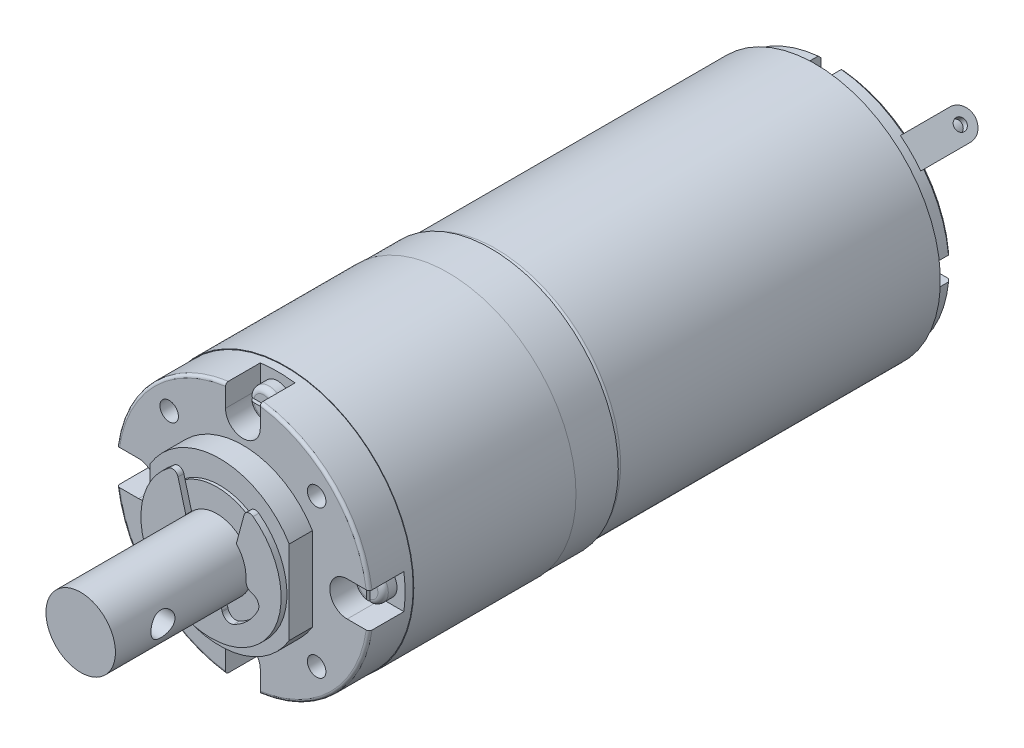
SolidWorks part; units mm, degrees
ref_plane "Front Plane" through (0, 0, 0) normal (0, 0, 1) x (1, 0, 0)
ref_plane "Top Plane" through (0, 0, 0) normal (0, 1, 0) x (1, 0, 0)
ref_plane "Right Plane" through (0, 0, 0) normal (1, 0, 0) x (0, 0, -1)
sketch "Sketch1" plane through (0, 0, 0) normal (0, 0, 1) x (1, 0, 0)
  circle A0 centre (0, 0) radius 11
  dimension "D1" = 22
extrude "Boss-Extrude1" add sketch "Sketch1" along normal mid plane 50.9
ref_plane "Plane1" through (0, 0, 4.05) normal (0, 0, -1) x (-1, 0, 0)
sketch "Sketch2" plane through (0, 0, 4.05) normal (0, 0, -1) x (-1, 0, 0)
  circle A0 centre (0, 0) radius 10.8
  circle A1 centre (0, 0) radius 11
  dimension "D1" = 22
  dimension "D2" = 21.6
extrude "Cut-Extrude1" cut sketch "Sketch2" along normal through all
ref_axis "Axis2" through (0, 0, -32.7585) along (0, 0, 1)
sketch "Sketch3" plane through (0, 0, 0) normal (1, 0, 0) x (0, 0, -1)
  line L0 (-4.05, 10.4) -> (-4.05, 10.3)
  line L1 (-3.55, 10.8) -> (-4.05, 10.8)
  line L2 (-4.05, -10.8) -> (-4.05, 10.8) construction
  line L3 (-4.05, 10.3) -> (-3.55, 10.3) construction
  line L4 (-3.55, 10.3) -> (-3.55, 10.8) construction
  line L5 (-3.55, 10.8) -> (-3.65, 10.8)
  line L6 (-4.05, -11) -> (-4.05, 11) construction
  line L7 (-4.05, 10.8) -> (-4.05, 10.3)
  arc A0 (-4.05, 10.4) -> (-3.65, 10.8) centre (-3.65, 10.4) cw
  dimension "D3" = 0.4
  dimension "D1" = 10.3
  dimension "D2" = 0.5
sketch "Sketch5" plane through (0, 0, 25.45) normal (0, 0, 1) x (1, 0, 0)
  line L0 (-1.5, 9) -> (-1.5, 10.8972)
  line L1 (1.5, 9) -> (1.5, 10.8972)
  line L2 (9, 1.5) -> (10.8972, 1.5)
  line L3 (9, -1.5) -> (10.8972, -1.5)
  line L4 (1.5, -9) -> (1.5, -10.8972)
  line L5 (-1.5, -9) -> (-1.5, -10.8972)
  line L6 (-9, -1.5) -> (-10.8972, -1.5)
  line L7 (-9, 1.5) -> (-10.8972, 1.5)
  circle A0 centre (0, 0) radius 9 construction
  arc A2 (-1.5, 9) -> (1.5, 9) centre (0, 9) ccw
  arc A3 (1.5, 10.8972) -> (-1.5, 10.8972) centre (0, 0) ccw
  arc A4 (9, 1.5) -> (9, -1.5) centre (9, 0) ccw
  arc A5 (10.8972, -1.5) -> (10.8972, 1.5) centre (0, 0) ccw
  arc A6 (1.5, -9) -> (-1.5, -9) centre (0, -9) ccw
  arc A7 (-1.5, -10.8972) -> (1.5, -10.8972) centre (0, 0) ccw
  arc A8 (-9, -1.5) -> (-9, 1.5) centre (-9, 0) ccw
  arc A9 (-10.8972, 1.5) -> (-10.8972, -1.5) centre (0, 0) ccw
  circle A10 centre (-6.364, 6.364) radius 0.8
  circle A11 centre (6.364, 6.364) radius 0.8
  circle A12 centre (6.364, -6.364) radius 0.8
  circle A13 centre (-6.364, -6.364) radius 0.8
  point P26 (0, 0)
  point P35 (0, 0)
  dimension "D1" = 18
  dimension "D2" = 1.5
  dimension "D3" = 11
  dimension "D6" = 1.6
  dimension "D5" = 45
  dimension "D4" = 4
  dimension "D7" = 4
extrude "Cut-Extrude2" cut sketch "Sketch5" against normal blind 3
revolve "Cut-Revolve3" cut sketch "Sketch3" angle 360 about axis through (0, 0, -32.7585) along (0, 0, 1)
sketch "Sketch6" plane through (0, 0, 25.45) normal (0, 0, 1) x (1, 0, 0)
  line L0 (-6, -3.6056) -> (-6, 3.6056)
  line L1 (6, -3.6056) -> (6, 3.6056)
  arc A0 (-6, -3.6056) -> (6, -3.6056) centre (0, 0) ccw
  arc A1 (6, 3.6056) -> (-6, 3.6056) centre (0, 0) ccw
  point P6 (-6, 0)
  point P9 (6, 0)
  dimension "D1" = 14
  dimension "D2" = 6
  dimension "D3" = 6
extrude "Boss-Extrude2" add sketch "Sketch6" along normal blind 2
sketch "Sketch7" plane through (0, 0, 27.45) normal (0, 0, 1) x (1, 0, 0)
  circle A0 centre (0, 0) radius 3
  dimension "D1" = 6
extrude "Boss-Extrude3" add sketch "Sketch7" along normal blind 12
ref_plane "Plane3" through (0, 0, 22.45) normal (0, 0, 1) x (1, 0, 0)
ref_plane "Plane4" through (0, 9, 0) normal (0, 1, 0) x (1, 0, 0)
sketch "Sketch9" plane through (0, 9, 0) normal (0, 1, 0) x (1, 0, 0)
  line L0 (0, -22.45) -> (0, -23.65)
  line L1 (-15.9774, -22.45) -> (15.9774, -22.45) construction
  line L2 (0, 32.7585) -> (0, -39.3925) construction
  line L3 (0, -23.65) -> (0.85, -23.65)
  line L4 (1.3, -23.2) -> (1.3, -22.45)
  line L5 (1.3, -22.45) -> (0, -22.45)
  arc A0 (1.3, -23.2) -> (0.85, -23.65) centre (0.85, -23.2) cw
  dimension "D1" = 0.45
  dimension "D2" = 1.3
  dimension "D3" = 1.2
revolve "Revolve1" add sketch "Sketch9" angle 360 about L0
sketch "Sketch10" plane through (0, 0, 23.65) normal (0, 0, 1) x (1, 0, 0)
  line L0 (0.15, 9.15) -> (1.2913, 9.15)
  line L2 (0, 7) -> (0, 11) construction
  line L4 (-1.2913, 8.85) -> (-0.15, 8.85)
  line L6 (-1.2913, 9.15) -> (-0.15, 9.15)
  line L8 (0.15, 8.85) -> (1.2913, 8.85)
  line L9 (2, 9) -> (-2, 9) construction
  line L10 (-0.15, 9.15) -> (0.15, 9.15)
  line L11 (0.15, 8.85) -> (-0.15, 8.85)
  arc A0 (-1.2913, 9.15) -> (-1.2913, 8.85) centre (0, 9) ccw
  arc A2 (1.2913, 8.85) -> (1.2913, 9.15) centre (0, 9) ccw
  point P18 (0, 9)
  point P21 (0, 9)
  dimension "D3" = 4
  dimension "D4" = 4
  dimension "D7" = 0.15
  dimension "D8" = 0.15
extrude "Cut-Extrude3" cut sketch "Sketch10" against normal blind 1
pattern_circular "CirPattern1" count 4 every 90 about axis through (0, 0, 0) along (0, 0, 1) of "Revolve1"
pattern_circular "CirPattern2" count 4 every 90 about axis through (0, 0, -32.7585) along (0, 0, 1) of "Cut-Extrude3"
sketch "Sketch11" plane through (0, 0, 27.45) normal (0, 0, 1) x (1, 0, 0)
  circle A0 centre (0, 0) radius 5
  dimension "D1" = 10
extrude "Boss-Extrude4" add sketch "Sketch11" along normal blind 0.25
ref_plane "Plane5" through (0, 0, 14.75) normal (0, 0, -1) x (-1, 0, 0)
sketch "Sketch12" plane through (0, 0, 14.75) normal (0, 0, -1) x (-1, 0, 0)
  circle A0 centre (0, 0) radius 11.05
extrude "Boss-Extrude5" add sketch "Sketch12" along normal mid plane 14
sketch "Sketch14" plane through (0, 0, 0) normal (1, 0, 0) x (0, 0, -1)
  line L0 (32.7585, 0) -> (-39.3925, 0) construction
  line L1 (-39.45, 3) -> (-39.45, -3) construction
  circle A0 centre (-35.35, 0) radius 1.0375
  dimension "D1" = 2.075
  dimension "D2" = 4.1
extrude "Cut-Extrude4" cut sketch "Sketch14" against normal mid plane 6
fillet "Fillet1" radius 0.25 4 edges at (-7.7782, -7.7782, 25.45) (7.7782, -7.7782, 25.45) (7.7782, 7.7782, 25.45) (-7.7782, 7.7782, 25.45)
sketch "Sketch15" plane through (0, 0, 27.7) normal (0, 0, 1) x (1, 0, 0)
  line L0 (2.1811, 2.0881) -> (3.0259, 5.241)
  line L1 (-2.1811, 2.0881) -> (-3.0259, 5.241)
  line L2 (0, -6.0518) -> (0, 11) construction
  line L3 (-3.6077, -0.9667) -> (-3.5285, -0.9455)
  line L4 (3.5285, -0.9455) -> (3.6077, -0.9667)
  line L5 (-0.9455, -3.5285) -> (-0.9667, -3.6077)
  line L6 (0.9455, -3.5285) -> (0.9667, -3.6077)
  arc A0 (-3.0259, 5.241) -> (3.0259, 5.241) centre (0, 0) ccw
  arc A1 (-2.1811, 2.0881) -> (-3.0116, -0.2186) centre (0, 0) ccw
  arc A2 (-4.0577, -1.9455) -> (-1.9455, -4.0577) centre (0, 0) ccw
  arc A3 (1.5, 10.8972) -> (-1.5, 10.8972) centre (0, 0) ccw construction
  arc A4 (3.0116, -0.2186) -> (2.1811, 2.0881) centre (0, 0) ccw
  arc A5 (-0.2186, -3.0116) -> (0.2186, -3.0116) centre (0, 0) ccw
  arc A6 (1.9455, -4.0577) -> (4.0577, -1.9455) centre (0, 0) ccw
  arc A7 (-3.0116, -0.2186) -> (-3.5285, -0.9455) centre (-3.7097, -0.2693) cw
  arc A8 (3.0116, -0.2186) -> (3.5285, -0.9455) centre (3.7097, -0.2693) ccw
  arc A9 (3.6077, -0.9667) -> (4.0577, -1.9455) centre (3.4265, -1.6428) cw
  arc A10 (-3.6077, -0.9667) -> (-4.0577, -1.9455) centre (-3.4265, -1.6428) ccw
  arc A11 (-0.9667, -3.6077) -> (-1.9455, -4.0577) centre (-1.6428, -3.4265) cw
  arc A12 (1.9455, -4.0577) -> (0.9667, -3.6077) centre (1.6428, -3.4265) cw
  arc A13 (0.2186, -3.0116) -> (0.9455, -3.5285) centre (0.2693, -3.7097) cw
  arc A14 (-0.2186, -3.0116) -> (-0.9455, -3.5285) centre (-0.2693, -3.7097) ccw
  point P22 (2.9166, -0.7815)
  point P25 (4.3467, -1.1647)
  point P32 (1.1647, -4.3467)
  point P37 (-0.7815, -2.9166)
  dimension "D7" = 0.7
  dimension "D8" = 4.5
  dimension "D1" = 15
  dimension "D2" = 15
  dimension "D3" = 75
  dimension "D4" = 75
  dimension "D5" = 15
  dimension "D6" = 15
extrude "Boss-Extrude6" add sketch "Sketch15" along normal blind 0.5
fillet "Fillet2" radius 0.5 2 edges at (3.0259, 5.241, 27.95) (-3.0259, 5.241, 27.95)
sketch "Sketch16" plane through (0, 0, -25.45) normal (0, 0, -1) x (-1, 0, 0)
  circle A0 centre (0, 0) radius 10.8
  circle A1 centre (0, 0) radius 10.3
  dimension "D1" = 21.6
  dimension "D2" = 20.6
extrude "Cut-Extrude5" cut sketch "Sketch16" against normal blind 1.5
sketch "Sketch17" plane through (0, 0, -25.45) normal (0, 0, -1) x (-1, 0, 0)
  line L0 (0, 8) -> (-1, 8)
  line L1 (-1, 8) -> (-1, 10.2513)
  line L2 (0, 0) -> (0, 12.1687) construction
  line L3 (0, 8) -> (1, 8)
  line L4 (1, 8) -> (1, 10.2513)
  line L5 (8, 1) -> (10.2513, 1)
  line L6 (8, 0) -> (8, 1)
  line L7 (8, 0) -> (8, -1)
  line L8 (8, -1) -> (10.2513, -1)
  line L9 (1, -8) -> (1, -10.2513)
  line L10 (0, -8) -> (1, -8)
  line L11 (0, -8) -> (-1, -8)
  line L12 (-1, -8) -> (-1, -10.2513)
  line L13 (-8, -1) -> (-10.2513, -1)
  line L14 (-8, 0) -> (-8, -1)
  line L15 (-8, 0) -> (-8, 1)
  line L16 (-8, 1) -> (-10.2513, 1)
  arc A0 (1, 10.2513) -> (-1, 10.2513) centre (0, 0) ccw
  arc A1 (10.2513, -1) -> (10.2513, 1) centre (0, 0) ccw
  arc A2 (-1, -10.2513) -> (1, -10.2513) centre (0, 0) ccw
  arc A3 (-10.2513, 1) -> (-10.2513, -1) centre (0, 0) ccw
  point P25 (0, 0)
  dimension "D1" = 10.3
  dimension "D2" = 8
  dimension "D3" = 1
  dimension "D4" = 1
  dimension "D5" = 4
extrude "Cut-Extrude6" cut sketch "Sketch17" against normal blind 0.5
sketch "Sketch18" plane through (0, 0, -25.45) normal (0, 0, -1) x (-1, 0, 0)
  line L0 (-1, 10.2513) -> (-1, 9.4472)
  line L2 (1, 10.2513) -> (1, 9.4472)
  line L4 (10.2513, 1) -> (9.4472, 1)
  line L5 (10.2513, -1) -> (9.4472, -1)
  line L6 (1, -10.2513) -> (1, -9.4472)
  line L7 (-1, -10.2513) -> (-1, -9.4472)
  line L8 (-10.2513, -1) -> (-9.4472, -1)
  line L9 (-10.2513, 1) -> (-9.4472, 1)
  arc A0 (1, 9.4472) -> (-1, 9.4472) centre (0, 0) ccw
  arc A1 (1, 10.2513) -> (-1, 10.2513) centre (0, 0) ccw
  arc A2 (9.4472, -1) -> (9.4472, 1) centre (0, 0) ccw
  arc A3 (10.2513, -1) -> (10.2513, 1) centre (0, 0) ccw
  arc A4 (-1, -9.4472) -> (1, -9.4472) centre (0, 0) ccw
  arc A5 (-1, -10.2513) -> (1, -10.2513) centre (0, 0) ccw
  arc A6 (-9.4472, 1) -> (-9.4472, -1) centre (0, 0) ccw
  arc A7 (-10.2513, 1) -> (-10.2513, -1) centre (0, 0) ccw
  point P23 (0, 0)
  dimension "D1" = 4
extrude "Cut-Extrude7" cut sketch "Sketch18" against normal blind 1.5
chamfer "Chamfer1" distance 0.25 angle 45 2 edges at (-7.2832, 7.2832, -25.45) (7.2832, -7.2832, -25.45)
sketch "Sketch19" plane through (0, 0, -25.45) normal (0, 0, -1) x (-1, 0, 0)
  line L0 (0, 0) -> (-7.4816, 7.4816) construction
  line L1 (-6.5453, 4.7776) -> (-8.3131, 6.5453)
  line L2 (-1, 8) -> (1, 8) construction
  line L3 (0, 0) -> (0, 8) construction
  line L4 (4.7776, -6.5453) -> (6.5453, -8.3131)
  line L5 (6.5453, -4.7776) -> (8.3131, -6.5453)
  line L6 (6.5453, -4.7776) -> (4.7776, -6.5453)
  line L14 (-4.7776, 6.5453) -> (-6.5453, 8.3131)
  line L15 (-6.5453, 4.7776) -> (-4.7776, 6.5453)
  arc A0 (6.5453, -8.3131) -> (8.3131, -6.5453) centre (0, 0) ccw
  arc A6 (-6.5453, 8.3131) -> (-8.3131, 6.5453) centre (0, 0) ccw
  point P1 (-7.6368, 7.6368)
  point P6 (-0.8839, -0.8839)
  point P7 (-8.5206, 6.7529)
  point P8 (0.8839, 0.8839)
  point P9 (-6.7529, 8.5206)
  point P13 (-5.6615, 5.6615)
  point P22 (0, 0)
  dimension "D1" = 45
  dimension "D3" = 8.0065
  dimension "D4" = 2.5
  dimension "D2" = 2
extrude "Cut-Extrude8" cut sketch "Sketch19" against normal blind 0.5
sketch "Sketch20" plane through (5.6615, 5.6615, 0) normal (0.7071, 0.7071, 0) x (0, 0, -1)
  line L0 (24.95, 1.25) -> (30.45, 1.25)
  line L1 (24.95, -1.25) -> (30.45, -1.25)
  line L2 (32.7585, 0) -> (-39.3925, 0) construction
  line L3 (24.95, -1.25) -> (24.95, 1.25) construction
  line L4 (24.95, -1.25) -> (24.95, 1.25)
  arc A0 (30.45, -1.25) -> (30.45, 1.25) centre (30.45, 0) ccw
  circle A1 centre (30.45, 0) radius 0.5
  dimension "D2" = 5.5
extrude "Boss-Extrude7" add sketch "Sketch20" along normal blind 0.5
pattern_circular "CirPattern4" count 2 every 180 about axis through (0, 0, 0) along (0, 0, 1) of "Boss-Extrude7"
sketch "Sketch22" plane through (0, 0, -25.45) normal (0, 0, -1) x (-1, 0, 0)
  circle A0 centre (0, 0) radius 3
  dimension "D1" = 6
extrude "Boss-Extrude8" add sketch "Sketch22" along normal blind 2
sketch "Sketch23" plane through (0, 0, -27.45) normal (0, 0, -1) x (-1, 0, 0)
  circle A0 centre (0, 0) radius 1
  dimension "D1" = 2
extrude "Boss-Extrude9" add sketch "Sketch23" along normal blind 9.2
chamfer "Chamfer2" distance 0.25 angle 45 1 edges at (-3, 0, -27.45)
